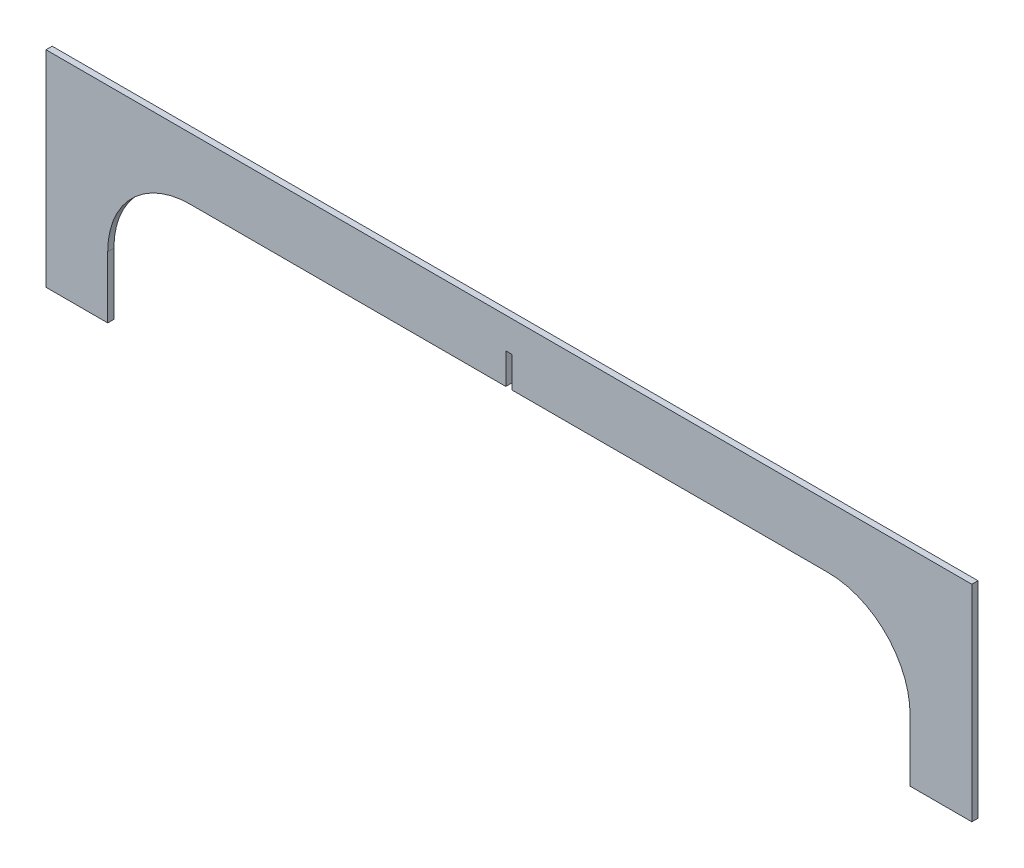
SolidWorks part; units mm, degrees
ref_plane "Front Plane" through (0, 0, 0) normal (0, 0, 1) x (1, 0, 0)
ref_plane "Top Plane" through (0, 0, 0) normal (0, 1, 0) x (1, 0, 0)
ref_plane "Right Plane" through (0, 0, 0) normal (1, 0, 0) x (0, 0, -1)
sketch "Sketch1" plane through (0, 0, 0) normal (0, 0, 1) x (1, 0, 0)
  line L0 (0, 0) -> (0, 100)
  line L1 (0, 100) -> (450, 100)
  line L2 (450, 100) -> (450, 0)
  line L3 (450, 0) -> (420, 0)
  line L4 (420, 0) -> (420, 70)
  line L5 (30, 70) -> (223.5, 70)
  line L6 (30, 70) -> (30, 0)
  line L7 (30, 0) -> (0, 0)
  line L8 (223.5, 70) -> (223.5, 85)
  line L9 (223.5, 85) -> (226.5, 85)
  line L10 (226.5, 85) -> (226.5, 70)
  line L11 (226.5, 70) -> (420, 70)
  dimension "D1" = 450
  dimension "D2" = 100
  dimension "D5" = 30
  dimension "D4" = 30
  dimension "D6" = 30
  dimension "D7" = 15
  dimension "D8" = 3
  dimension "D3" = 30
  dimension "D9" = 390
  dimension "D10" = 193.5
  dimension "D11" = 193.5
extrude "Boss-Extrude1" add sketch "Sketch1" along normal blind 3
fillet "Fillet1" radius 40 2 edges at (420, 70, 1.5) (30, 70, 1.5)
equation "\"D10@Sketch1\"=(\"D9@Sketch1\"-\"D8@Sketch1\")/2"
